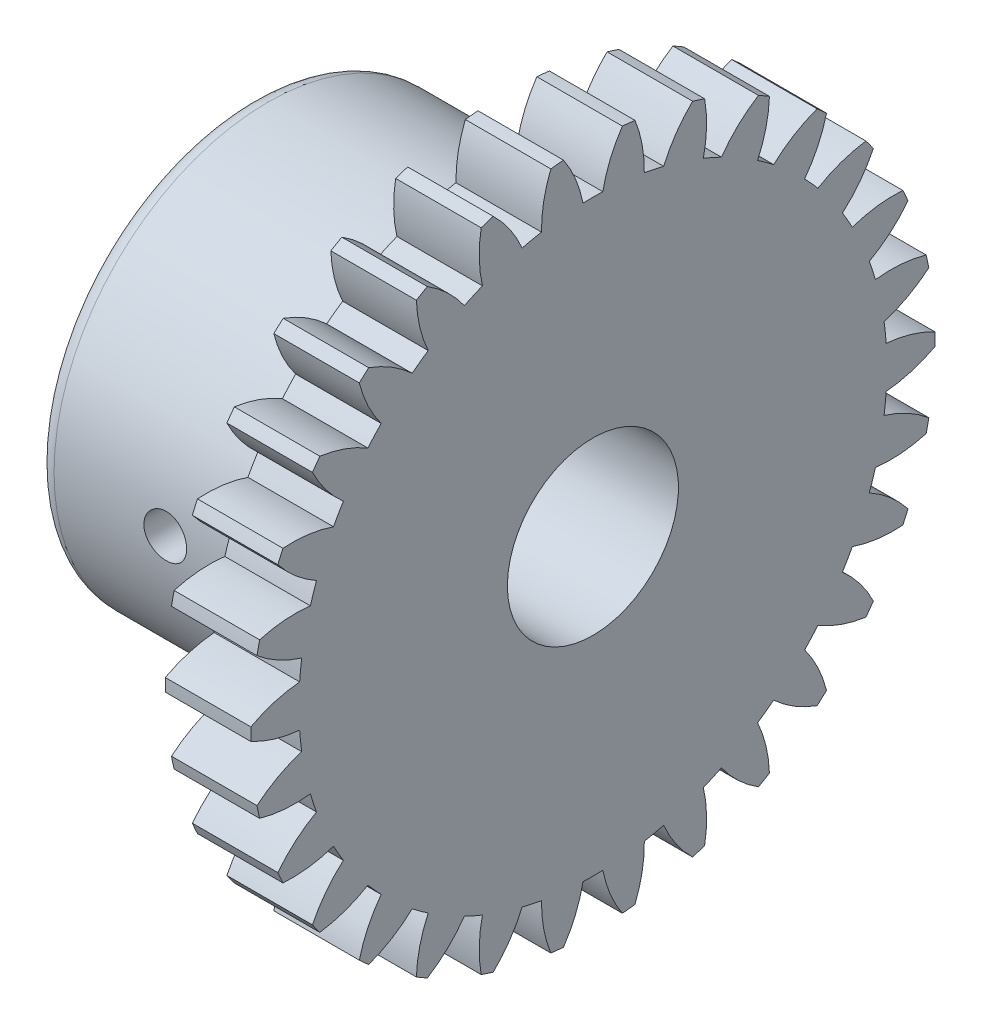
SolidWorks part; units mm, degrees
material "ABS"
ref_plane "Plane1" through (0, 0, 0) normal (0, 0, 1) x (1, 0, 0)
ref_plane "Plane2" through (0, 0, 0) normal (0, 1, 0) x (1, 0, 0)
ref_plane "Plane3" through (0, 0, 0) normal (1, 0, 0) x (0, 0, -1)
sketch "HoldingSke" plane through (0, 0, 0) normal (0, 1, 0) x (1, 0, 0)
  line L0 (0, 0) -> (351.9527, -203.2)
  line L1 (-15, 0) -> (100, 0) construction
  line L2 (0, 0) -> (-2.1039, 2.3779)
  line L3 (0, 0) -> (-11.863, 4.5341)
  line L4 (0, 0) -> (7.479, 4.318)
  line L5 (0, 0) -> (-23.7986, -8.8762)
  line L6 (0, 0) -> (-5.2639, -3.5516)
  line L7 (-2.1039, 2.3779) -> (3.3635, 27.1825)
  line L8 (-76.2, 54.61) -> (-61.976, 54.61)
  line L9 (-71.009, 38.7566) -> (-53.1078, 45.2721)
  line L10 (-76.2, 71.12) -> (104.1128, 71.12)
  line L11 (0, 0) -> (-6.35, 0)
  line L12 (-76.2, 101.6) -> (-76.1428, 101.6)
  line L13 (24.9733, 27.94) -> (52.9518, 28.4284)
  line L14 (24.9733, 27.94) -> (24.9746, 27.94)
  line L15 (24.9733, 27.94) -> (100.4006, 29.5858)
  circle A0 centre (0, 0) radius 6.35
  circle A1 centre (0, 0) radius 15.875
  circle A2 centre (0, 0) radius 15.875
  circle A3 centre (0, 0) radius 6.35
  dimension "MHD" = 31.75
  dimension "Hub_dia" = 31.75
  dimension "Bore" = 12.7
  dimension "MBD" = 12.7
  dimension "Num_teeth" = 30
  dimension "Pitch_radius" = 180.3128
  dimension "Pitch" = 406.4
  dimension "Width" = 6.35
  dimension "Overall_len" = 25.4
  dimension "Show_teeth" = 30
  dimension "Thickness" = 6.35
  dimension "OAL" = 25.4001
  dimension "T_dim" = 14.224
  dimension "Ap" = 20
  dimension "H" = 19.05
  dimension "Backlash" = 0.0571
  dimension "Addendum_fac" = 1
  dimension "Dedendum_fac" = 1.25
  dimension "Clearance_fac" = 0.25
  dimension "Dedendum_add" = 0.0013
sketch "BasProSke" plane through (0, 0, 0) normal (0, 1, 0) x (1, 0, 0)
  line L0 (-10, 0) -> (60, 0) construction
  line L1 (0, 0) -> (0, 25.4)
  line L2 (0, 0) -> (6.35, 0)
  line L3 (6.35, 0) -> (6.35, 25.4)
  line L4 (6.35, 25.4) -> (0, 25.4)
  dimension "Diameter" = 50.8
  dimension "Thickness" = 6.35
revolve "Base-Revolve" add sketch "BasProSke" angle 360 about L0
sketch "TooCutSke" plane through (0, 0, 0) normal (1, 0, 0) x (0, 0, -1)
  line L1 (0, 0) -> (0, 107) construction
  line L2 (0, 0) -> (-1.3462, 23.7744) construction
  line L3 (0, 0) -> (-4.9724, 47.3092) construction
  line L4 (-1.3462, 23.7744) -> (-2.4862, 23.6546) construction
  arc A0 (0.7354, 21.8145) -> (-0.7354, 21.8145) centre (0, 0) ccw
  arc A1 (2.2029, 25.3298) -> (-2.2029, 25.3298) centre (0, 0) ccw
  circle A2 centre (0, 0) radius 23.8125 construction
  circle A3 centre (0, 0) radius 22.3764 construction
  arc A4 (-0.7354, 21.8145) -> (-2.2029, 25.3298) centre (-10.0814, 19.9767) ccw
  arc A5 (2.2029, 25.3298) -> (0.7354, 21.8145) centre (10.0814, 19.9767) ccw
  dimension "Root_dia" = 43.6537
  dimension "Overcut_dia" = 50.8508
  dimension "Pitch_dia" = 47.625
  dimension "Base_dia" = 44.7529
  dimension "Flank_rad" = 9.525
  dimension "Half_ang" = 6
  dimension "Half_CT" = 1.1462
extrude "ToothCut" cut sketch "TooCutSke" along normal through all
fillet "Breaks" [suppressed] radius 0.0318
fillet "RootFillets" [suppressed] radius 0.3981
pattern_circular "TeethCuts" count 30 every 12 about axis through (-10, 0, 0) along (1, 0, 0) of "ToothCut", "RootFillets", "Breaks"
sketch "HubNeaOneSke" plane through (0, 0, 0) normal (-1, 0, 0) x (0, 0, 1)
  circle A0 centre (0, 0) radius 15.875
  dimension "Diameter" = 31.75
extrude "HubNearOne" add sketch "HubNeaOneSke" along normal blind 19.0501
sketch "HubNeaBotSke" plane through (0, 0, 0) normal (-1, 0, 0) x (0, 0, 1)
  circle A0 centre (0, 0) radius 15.875
  dimension "Diameter" = 31.75
extrude "HubNearBoth" [suppressed] add sketch "HubNeaBotSke" along normal blind 9.525
ref_plane "FarPln" through (6.35, 0, 0) normal (1, 0, 0) x (0, 0, -1)
sketch "HubFarSke" plane through (6.35, 0, 0) normal (1, 0, 0) x (0, 0, -1)
  circle A0 centre (0, 0) radius 15.875
  dimension "Diameter" = 31.75
extrude "HubFar" [suppressed] add sketch "HubFarSke" along normal blind 9.525
sketch "BorSke" plane through (0, 0, 0) normal (1, 0, 0) x (0, 0, -1)
  circle A0 centre (0, 0) radius 6.35
  dimension "Diameter" = 12.7
extrude "Bore" cut sketch "BorSke" along normal mid plane 50.8001
sketch "KeySke" plane through (0, 0, 0) normal (1, 0, 0) x (0, 0, -1)
  line L0 (-1.5875, 0) -> (-1.5875, 7.874)
  line L1 (-1.5875, 7.874) -> (1.5875, 7.874)
  line L2 (1.5875, 7.874) -> (1.5875, 0)
  line L3 (0, 0) -> (0, 34) construction
  line L4 (-1.5875, 0) -> (1.5875, 0)
  dimension "Offset" = 7.874
  dimension "Width" = 3.175
extrude "Keyway" [suppressed] cut sketch "KeySke" along normal mid plane 50.8001
pattern_circular "Keyway2" [suppressed] count 2 every 90 about axis through (-10, 0, 0) along (1, 0, 0)
sketch "Sketch1" plane through (0, 0, 0) normal (0, 0, 1) x (1, 0, 0)
  line L0 (0, 0) -> (-19.0501, 0) construction
  line L1 (0, 15.875) -> (0, -15.875) construction
  line L2 (-19.0501, 15.875) -> (-19.0501, -15.875) construction
  circle A0 centre (-9.525, 0) radius 1.5875
  dimension "D1" = 3.175
extrude "Cut-Extrude1" cut sketch "Sketch1" against normal through all and the other way through all
fillet "Fillet1" radius 1.27 2 edges at (-19.0501, 0, 15.875) (0, 0, -15.875)
equation "' \"Pitch@HoldingSke\" = 4"
equation "' \"Num_teeth@HoldingSke\" = 12"
equation "' \"Ap@HoldingSke\" =  20"
equation "' \"Width@HoldingSke\" = 0.5"
equation "' \"Hub_dia@HoldingSke\"= 1"
equation "' \"Overall_len@HoldingSke\" = 1.0"
equation "' \"Bore@HoldingSke\" = 0.75"
equation "' \"T_dim@HoldingSke\" = 0.85"
equation "' \"Width@KeySke\" = 0.25"
equation "' \"Show_teeth@HoldingSke\" = 13"
equation "' \"Backlash@HoldingSke\" = 0.009"
equation "' \"Addendum_fac@HoldingSke\" = 1.0"
equation "' \"Dedendum_fac@HoldingSke\" = 1.25"
equation "' \"Dedendum_add@HoldingSke\" = 0.00005"
equation "' \"Clearance_fac@HoldingSke\" = 0.25"
equation "' \"Pitch@HoldingSke\" = 0.5"
equation "' \"Num_teeth@HoldingSke\" = 23"
equation "' \"Show_teeth@HoldingSke\" = 23"
equation "' \"Backlash@HoldingSke\" = 0.0375"
equation "\"Overcut_dia@TooCutSke\" = (\"Num_teeth@HoldingSke\" + 2 * \"Addendum_fac@HoldingSke\") / \"Pitch@HoldingSke\" + 0.002"
equation "\"Pitch_dia@TooCutSke\" = \"Num_teeth@HoldingSke\" / \"Pitch@HoldingSke\""
equation "\"Base_dia@TooCutSke\" = \"Num_teeth@HoldingSke\" / \"Pitch@HoldingSke\" * cos((\"Ap@HoldingSke\"  * 3.14159265 / 180))"
equation "\"Root_dia@TooCutSke\" = (\"Num_teeth@HoldingSke\" + 2) / \"Pitch@HoldingSke\" - 2 * (\"Addendum_fac@HoldingSke\" + \"Dedendum_fac@HoldingSke\") / \"Pitch@HoldingSke\" - \"Dedendum_add@HoldingSke\" * 2"
equation "\"Half_ang@TooCutSke\" = 180 / \"Num_teeth@HoldingSke\""
equation "\"Half_CT@TooCutSke\" = \"Num_teeth@HoldingSke\" / \"Pitch@HoldingSke\" * sin((3.14159265 / 2 / \"Num_teeth@HoldingSke\")) / 2 - 7 * \"Backlash@HoldingSke\" / 4"
equation "\"Flank_rad@TooCutSke\" = \"Num_teeth@HoldingSke\" / \"Pitch@HoldingSke\" / 5"
equation "\"Radius@RootFillets\" = \"Clearance_fac@HoldingSke\" / \"Pitch@HoldingSke\" + \"Dedendum_add@HoldingSke\""
equation "\"Break_rad@Breaks\" = 0.02 / \"Pitch@HoldingSke\""
equation "\"Thickness@HoldingSke\" = \"Width@HoldingSke\""
equation "\"OAL@HoldingSke\" = \"Thickness@HoldingSke\""
equation "\"MHD@HoldingSke\" = (\"Num_teeth@HoldingSke\" + 2) / \"Pitch@HoldingSke\" - 2 * (\"Addendum_fac@HoldingSke\" + \"Dedendum_fac@HoldingSke\")  / \"Pitch@HoldingSke\" - \"Dedendum_add@HoldingSke\" * 2"
equation "\"MBD@HoldingSke\" = (\"Num_teeth@HoldingSke\" + 2) / \"Pitch@HoldingSke\" - 2 * (\"Addendum_fac@HoldingSke\" + \"Dedendum_fac@HoldingSke\")  / \"Pitch@HoldingSke\" - \"Dedendum_add@HoldingSke\" * 2 - 0.002"
equation "\"MHD@HoldingSke\" = ((sgn( \"MHD@HoldingSke\" - \"Hub_dia@HoldingSke\" )-1)*( \"MHD@HoldingSke\" - \"Hub_dia@HoldingSke\" ))/-2+ \"Hub_dia@HoldingSke\""
equation "\"MBD@HoldingSke\" = ((sgn( \"MBD@HoldingSke\" - \"Bore@HoldingSke\" )-1)*( \"MBD@HoldingSke\" - \"Bore@HoldingSke\" ))/-2+ \"Bore@HoldingSke\""
equation "\"OAL@HoldingSke\" = ((sgn( \"OAL@HoldingSke\" - \"Overall_len@HoldingSke\" )+1)*( \"OAL@HoldingSke\" - \"Overall_len@HoldingSke\" ))/2 + \"Overall_len@HoldingSke\" + 0.000002"
equation "\"Num_teeth@TeethCuts\" = int( \"Show_teeth@HoldingSke\" ) + 1"
equation "\"Num_teeth@TeethCuts\" = ((sgn( \"Num_teeth@TeethCuts\" - \"Num_teeth@HoldingSke\" )-1)*( \"Num_teeth@TeethCuts\" - \"Num_teeth@HoldingSke\" ))/-2+ \"Num_teeth@HoldingSke\""
equation "\"Num_teeth@TeethCuts\" = ((sgn( \"Num_teeth@TeethCuts\" - 2.0)+1)*( \"Num_teeth@TeethCuts\" - 2.0))/2 +2.0"
equation "\"Angle@TeethCuts\" = 360.0 / \"Num_teeth@HoldingSke\""
equation "\"Diameter@BasProSke\" = (\"Num_teeth@HoldingSke\" + 2 * \"Addendum_fac@HoldingSke\") / \"Pitch@HoldingSke\""
equation "\"Thickness@BasProSke\"  = \"Thickness@HoldingSke\""
equation "' \"Fillet_rad@BasProSke\" =  \"Thickness@HoldingSke\" * 0.05"
equation "\"MHD@HoldingSke\" = ((sgn( \"MHD@HoldingSke\" - \"Root_dia@TooCutSke\" )-1)*( \"MHD@HoldingSke\" - \"Root_dia@TooCutSke\" ))/-2+ \"Root_dia@TooCutSke\""
equation "\"Diameter@HubNeaOneSke\" = \"MHD@HoldingSke\""
equation "\"Length@HubNearOne\" = \"OAL@HoldingSke\" - \"Thickness@BasProSke\""
equation "\"Diameter@HubNeaBotSke\" = \"MHD@HoldingSke\""
equation "\"Length@HubNearBoth\" = ( \"OAL@HoldingSke\" - \"Thickness@BasProSke\" ) / 2.0"
equation "\"Thickness@FarPln\" = \"Thickness@BasProSke\""
equation "\"Diameter@HubFarSke\" = \"MHD@HoldingSke\""
equation "\"Length@HubFar\" = ( \"OAL@HoldingSke\" - \"Thickness@BasProSke\" ) / 2.0"
equation "\"Diameter@BorSke\" = \"MBD@HoldingSke\""
equation "\"D1@Bore\" = \"OAL@HoldingSke\" * 2.0"
equation "\"D1@Keyway\" = \"OAL@HoldingSke\" * 2.0"
equation "\"Offset@KeySke\" = \"T_dim@HoldingSke\" - \"MBD@HoldingSke\" / 2.0"
